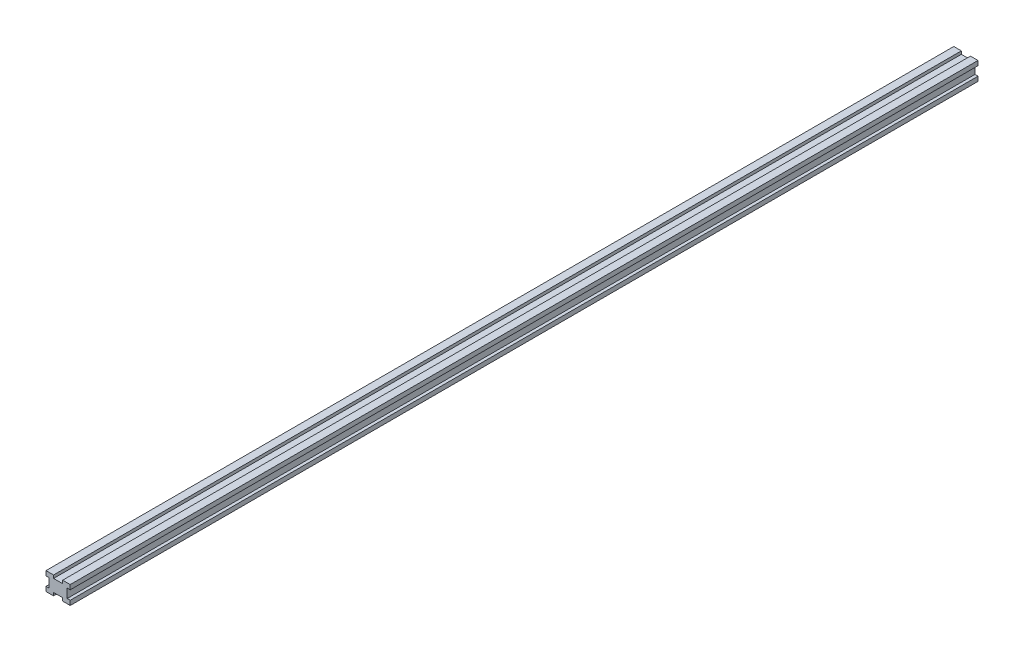
SolidWorks part; units mm, degrees
ref_plane "Front Plane" through (0, 0, 0) normal (0, 0, 1) x (1, 0, 0)
ref_plane "Top Plane" through (0, 0, 0) normal (0, 1, 0) x (1, 0, 0)
ref_plane "Right Plane" through (0, 0, 0) normal (1, 0, 0) x (0, 0, -1)
sketch "Sketch2" plane through (0, 0, 0) normal (0, 0, 1) x (1, 0, 0)
  line L1 (-20, -15) -> (20, -15)
  line L2 (-20, -15) -> (-20, 15)
  line L3 (-20, 15) -> (20, 15)
  line L4 (20, -15) -> (20, 15)
  line L5 (-20, -15) -> (20, 15) construction
  line L6 (-20, 15) -> (20, -15) construction
  point P0 (0, 0)
  dimension "D1" = 40
  dimension "D2" = 30
extrude "Boss-Extrude2" add sketch "Sketch2" along normal blind 1500
sketch "Sketch3" plane through (0, 0, 1500) normal (0, 0, 1) x (1, 0, 0)
  line L0 (-7.5, 15) -> (-7.5, 10)
  line L1 (20, 15) -> (-20, 15) construction
  line L2 (-7.5, 10) -> (7.5, 10)
  line L3 (7.5, 10) -> (7.5, 15)
  line L4 (20, 7.5) -> (15, 7.5)
  line L5 (20, -15) -> (20, 15) construction
  line L6 (15, 7.5) -> (15, -7.5)
  line L7 (15, -7.5) -> (20, -7.5)
  line L8 (-7.5, -15) -> (-7.5, -10)
  line L9 (-20, -15) -> (20, -15) construction
  line L10 (-7.5, -10) -> (7.5, -10)
  line L11 (7.5, -10) -> (7.5, -15)
  line L12 (-20, 7.5) -> (-15, 7.5)
  line L13 (-20, 15) -> (-20, -15) construction
  line L14 (-15, 7.5) -> (-15, -7.5)
  line L15 (-15, -7.5) -> (-20, -7.5)
  line L16 (-7.5, 15) -> (7.5, 15)
  line L17 (20, 7.5) -> (20, -7.5)
  line L18 (-7.5, -15) -> (7.5, -15)
  line L19 (-20, 7.5) -> (-20, -7.5)
  dimension "D1" = 5
  dimension "D2" = 15
  dimension "D3" = 15
  dimension "D4" = 5
  dimension "D5" = 15
  dimension "D6" = 5
  dimension "D7" = 15
  dimension "D8" = 5
  dimension "D9" = 7.5
  dimension "D10" = 12.5
extrude "Cut-Extrude1" cut sketch "Sketch3" against normal blind 1500
